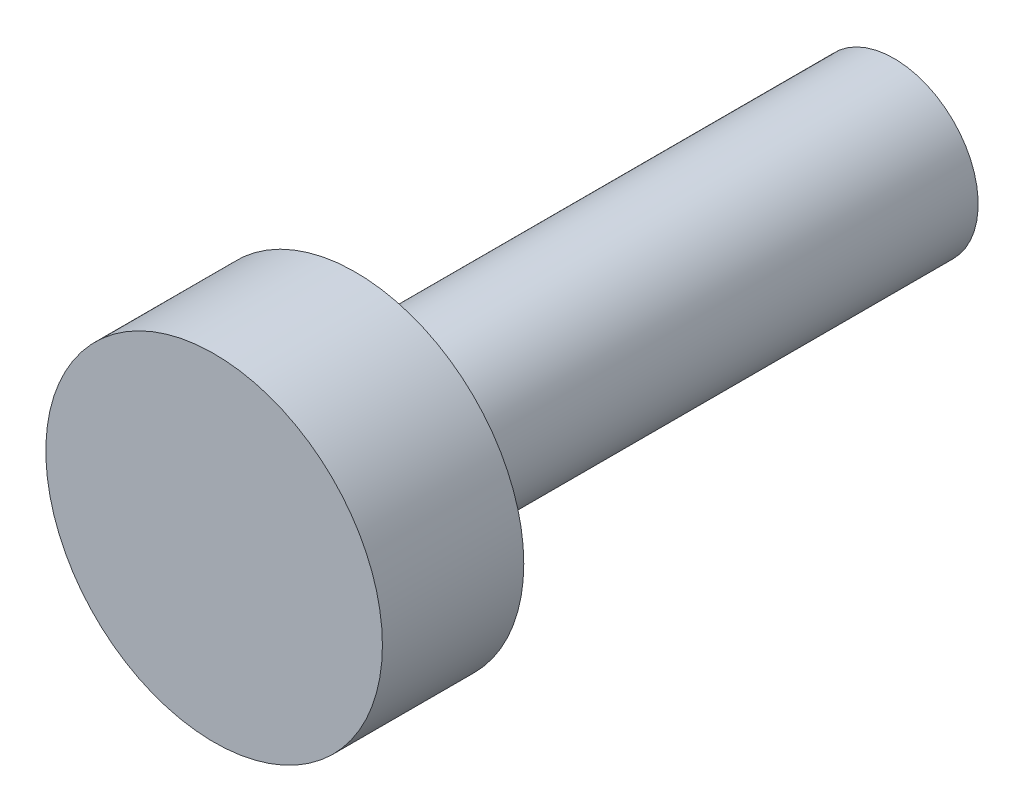
SolidWorks part; units mm, degrees
ref_plane "Plan de face" through (0, 0, 0) normal (0, 0, 1) x (1, 0, 0)
ref_plane "Plan de dessus" through (0, 0, 0) normal (0, 1, 0) x (1, 0, 0)
ref_plane "Plan de droite" through (0, 0, 0) normal (1, 0, 0) x (0, 0, -1)
sketch "Esquisse1" plane through (0, 0, 0) normal (0, 0, 1) x (1, 0, 0)
  circle A0 centre (0, 0) radius 2.5
  dimension "D1" = 5
extrude "Boss.-Extru.1" add sketch "Esquisse1" along normal blind 2.1
sketch "Esquisse2" plane through (0, 0, 0) normal (0, 0, -1) x (-1, 0, 0)
  circle A0 centre (0, 0) radius 1.25
  dimension "D1" = 2.5
extrude "Boss.-Extru.2" add sketch "Esquisse2" along normal blind 8
